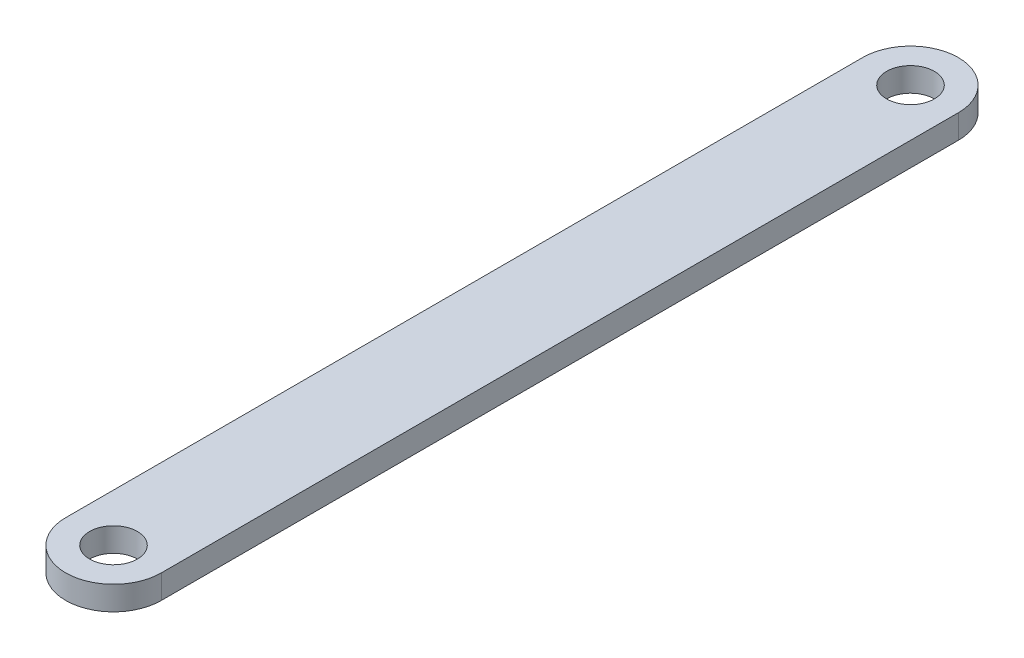
SolidWorks part; units mm, degrees
ref_plane "Front Plane" through (0, 0, 0) normal (0, 0, 1) x (1, 0, 0)
ref_plane "Top Plane" through (0, 0, 0) normal (0, 1, 0) x (1, 0, 0)
ref_plane "Right Plane" through (0, 0, 0) normal (1, 0, 0) x (0, 0, -1)
sketch "Sketch1" plane through (0, 0, 0) normal (0, 1, 0) x (1, 0, 0)
  line L1 (0, 0) -> (6, 0) construction
  line L2 (0, 0) -> (0, -50)
  line L3 (0, -50) -> (6, -50) construction
  line L4 (6, 0) -> (6, -50)
  arc A0 (6, 0) -> (0, 0) centre (3, 0) ccw
  arc A1 (0, -50) -> (6, -50) centre (3, -50) ccw
  arc A2 (0, 0) -> (6, 0) centre (3, 0) ccw construction
  arc A3 (6, -50) -> (0, -50) centre (3, -50) ccw construction
  circle A4 centre (3, 0) radius 1.5
  circle A5 centre (3, -50) radius 1.5
  dimension "D3" = 3
  dimension "D1" = 50
  dimension "D2" = 6
extrude "Boss-Extrude1" add sketch "Sketch1" along normal blind 1.5
